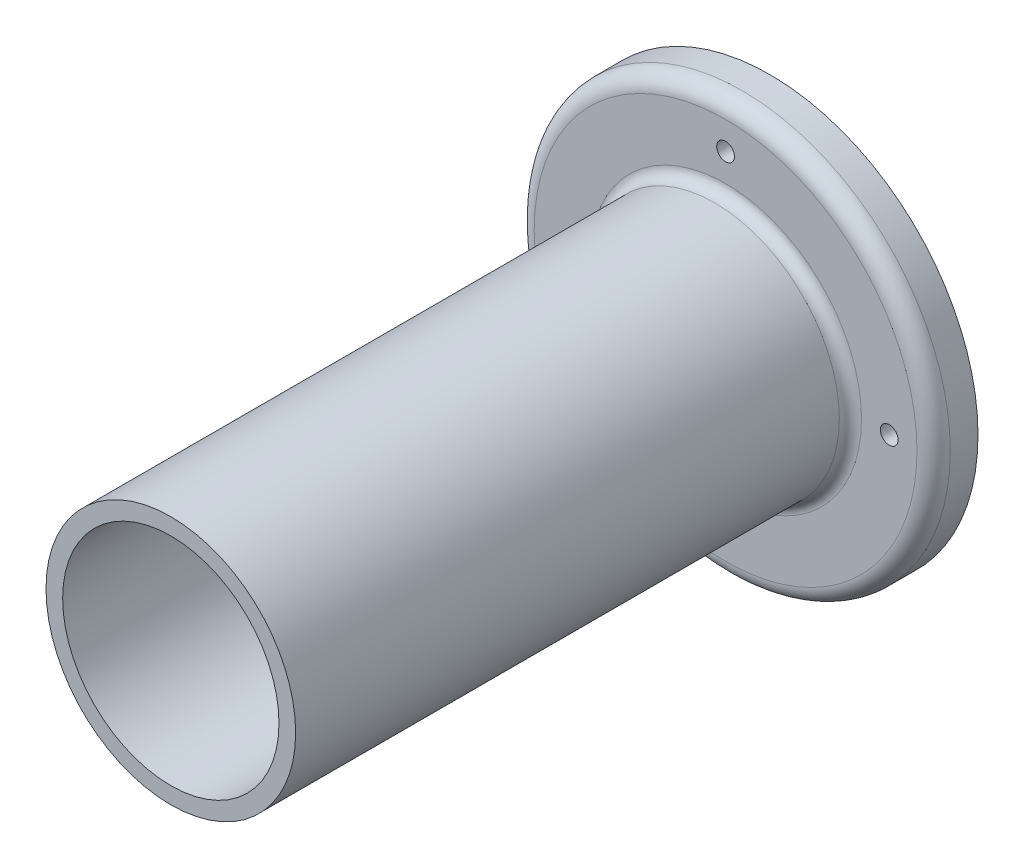
SolidWorks part; units mm, degrees
ref_plane "Płaszczyzna przednia" through (0, 0, 0) normal (0, 0, 1) x (1, 0, 0)
ref_plane "Płaszczyzna górna" through (0, 0, 0) normal (0, 1, 0) x (1, 0, 0)
ref_plane "Płaszczyzna prawa" through (0, 0, 0) normal (1, 0, 0) x (0, 0, -1)
sketch "Szkic1" plane through (0, 0, 0) normal (0, 0, 1) x (1, 0, 0)
  circle A0 centre (0, 0) radius 29.5 construction
  circle A1 centre (0, 29.5) radius 1.6
  circle A2 centre (29.5, 0) radius 1.6
  circle A3 centre (0, -29.5) radius 1.6
  circle A4 centre (-29.5, 0) radius 1.6
  circle A5 centre (0, 0) radius 37.5
  point P6 (-28.6975, 0.9153)
  point P7 (0, 0)
  point P14 (0, 0)
  point P18 (0, 0)
  point P19 (0, 0)
  point P20 (0, 0)
  point P21 (0, 0)
  dimension "D1" = 59
  dimension "D2" = 3.2
  dimension "D4" = 75
  dimension "D3" = 4
extrude "Dodanie-wyciągnięcie1" add sketch "Szkic1" along normal blind 8
fillet "Zaokrąglenie1" radius 3 1 edges at (37.5, 0, 8)
sketch "Szkic2" plane through (0, 0, 8) normal (0, 0, 1) x (1, 0, 0)
  circle A0 centre (0, 0) radius 22.5
  circle A1 centre (0, 0) radius 19.5
  dimension "D1" = 45
  dimension "D2" = 39
extrude "Dodanie-wyciągnięcie2" add sketch "Szkic2" along normal blind 100
fillet "Zaokrąglenie2" radius 2 1 edges at (22.5, 0, 8)
